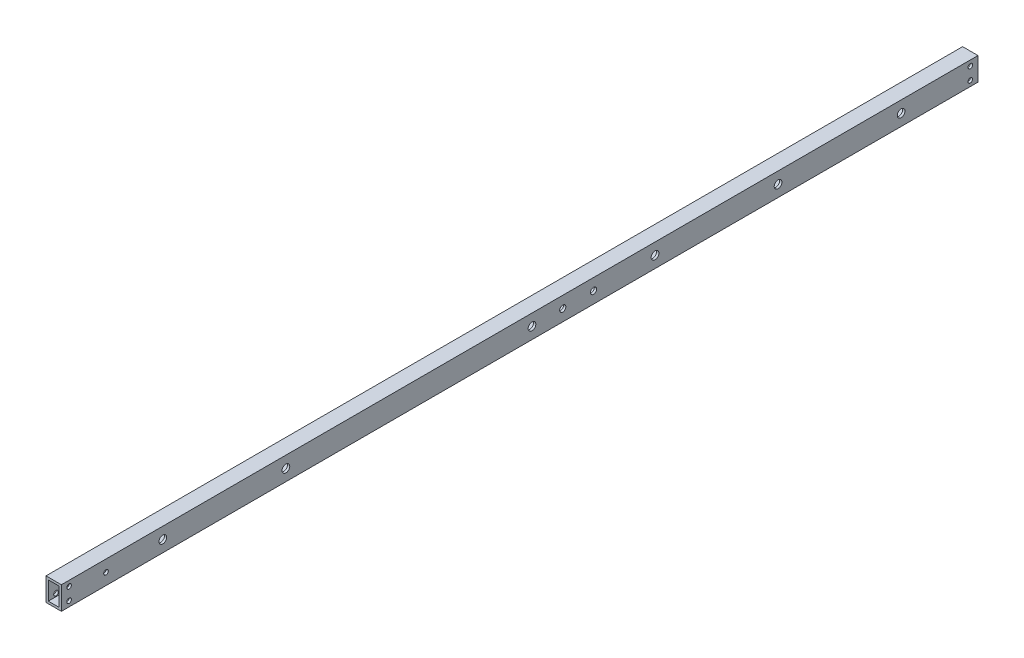
SolidWorks part; units mm, degrees
ref_plane "正面" through (0, 0, 0) normal (0, 0, 1) x (1, 0, 0)
ref_plane "平面" through (0, 0, 0) normal (0, 1, 0) x (1, 0, 0)
ref_plane "右側面" through (0, 0, 0) normal (1, 0, 0) x (0, 0, -1)
sketch "ｽｹｯﾁ1" plane through (0, 0, 0) normal (0, 0, 1) x (1, 0, 0)
  line L1 (-5, -7.5) -> (5, -7.5)
  line L2 (-5, -7.5) -> (-5, 7.5)
  line L3 (-5, 7.5) -> (5, 7.5)
  line L4 (5, -7.5) -> (5, 7.5)
  line L5 (-5, -7.5) -> (5, 7.5) construction
  line L6 (-5, 7.5) -> (5, -7.5) construction
  point P0 (0, 0)
  dimension "D1" = 15
  dimension "D2" = 10
extrude "押し出し-薄板1" add sketch "ｽｹｯﾁ1" along normal blind 596 thin thin type one direction reverse wall 1.5
sketch "ｽｹｯﾁ2" plane through (5, 0, 0) normal (1, 0, 0) x (0, 0, -1)
  line L0 (-539, 0) -> (49461, 0) construction
  line L1 (-596, -7.5) -> (-596, 7.5) construction
  line L2 (0, -7.5) -> (0, 7.5) construction
  line L4 (-260, 7.5) -> (-260, -7.5) construction
  line L5 (-596, 7.5) -> (0, 7.5) construction
  line L6 (-596, -7.5) -> (0, -7.5) construction
  circle A1 centre (-5, 4) radius 1.5
  circle A2 centre (-5, -4) radius 1.5
  circle A3 centre (-591, 4) radius 1.5
  circle A4 centre (-591, -4) radius 1.5
  circle A5 centre (-50, 0) radius 2.5
  circle A6 centre (-567, 0) radius 1.5
  circle A7 centre (-530, 0) radius 2.5
  circle A8 centre (-250, 0) radius 2
  circle A9 centre (-270, 0) radius 2
  circle A10 centre (-450, 0) radius 2.5
  circle A12 centre (-290, 0) radius 2.5
  circle A14 centre (-210, 0) radius 2.5
  circle A15 centre (-130, 0) radius 2.5
  point P4 (-596, 0)
  dimension "D1" = 3
  dimension "D2" = 8
  dimension "D3" = 8
  dimension "D4" = 5
  dimension "D5" = 3
  dimension "D6" = 5
  dimension "D7" = 50
  dimension "D8" = 5
  dimension "D9" = 29
  dimension "D10" = 3
  dimension "D12" = 66
  dimension "D14" = 20
  dimension "D15" = 4
  dimension "D16" = 5
  dimension "D17" = 80
  dimension "D18" = 5
  dimension "D19" = 30
  dimension "D20" = 50
  dimension "D21" = 80
  dimension "D11" = 0
  dimension "D13" = 260
extrude "ｶｯﾄ - 押し出し1" cut sketch "ｽｹｯﾁ2" against normal through all
sketch "ｽｹｯﾁ3" plane through (-5, 0, 0) normal (-1, 0, 0) x (0, 0, 1)
  circle A0 centre (250, 0) radius 4
  circle A1 centre (270, 0) radius 4
  dimension "D1" = 8
extrude "ｶｯﾄ - 押し出し2" cut sketch "ｽｹｯﾁ3" against normal up to surface (1.5 mm away) up to face at (-3.5, 0, 268)
